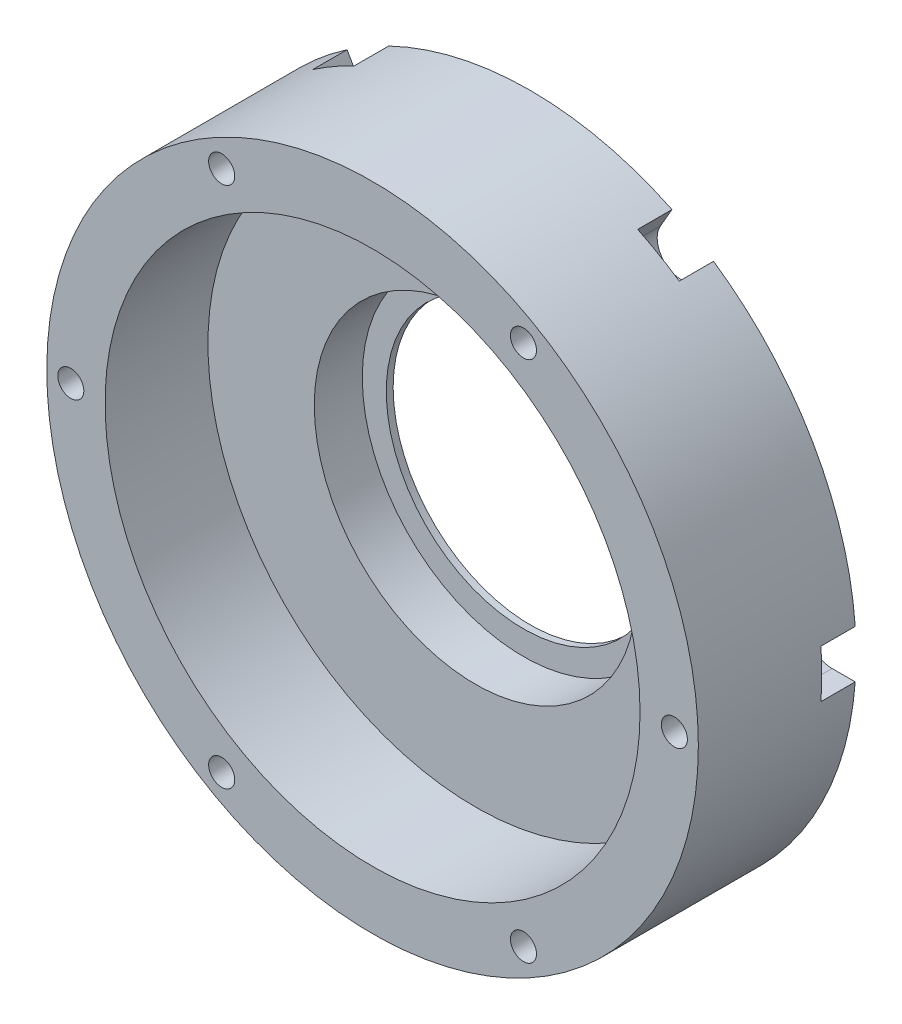
SolidWorks part; units mm, degrees
ref_plane "Front Plane" through (0, 0, 0) normal (0, 0, 1) x (1, 0, 0)
ref_plane "Top Plane" through (0, 0, 0) normal (0, 1, 0) x (1, 0, 0)
ref_plane "Right Plane" through (0, 0, 0) normal (1, 0, 0) x (0, 0, -1)
sketch "Sketch1" plane through (0, 0, 0) normal (0, 0, 1) x (1, 0, 0)
  circle A0 centre (0, 0) radius 47.5
  circle A1 centre (0, 0) radius 39
  dimension "D1" = 95
  dimension "D2" = 8.5
extrude "Boss-Extrude1" add sketch "Sketch1" along normal blind 15
sketch "Sketch4" plane through (0, 0, 0) normal (0, 0, -1) x (-1, 0, 0)
  circle A0 centre (0, 0) radius 47.5
  circle A1 centre (0, 0) radius 20
  dimension "D1" = 40
extrude "Boss-Extrude2" add sketch "Sketch4" along normal blind 8
sketch "Sketch5" plane through (0, 0, 0) normal (0, 0, 1) x (1, 0, 0)
  circle A0 centre (0, 0) radius 23.5
  dimension "D1" = 47
extrude "Cut-Extrude3" cut sketch "Sketch5" against normal blind 7
sketch "Sketch6" plane through (0, 0, 15) normal (0, 0, 1) x (1, 0, 0)
  circle A1 centre (44, 0) radius 1.9
  circle A2 centre (0, 0) radius 44
  circle A3 centre (0, 0) radius 44 construction
  circle A4 centre (22, -38.1051) radius 1.9
  circle A5 centre (-22, -38.1051) radius 1.9
  circle A6 centre (-44, 0) radius 1.9
  circle A7 centre (-22, 38.1051) radius 1.9
  circle A8 centre (22, 38.1051) radius 1.9
  point P17 (0, 0)
  dimension "D2" = 3.8
  dimension "D1" = 3.5
  dimension "D3" = 6
extrude "Cut-Extrude4" cut sketch "Sketch6" against normal through all
sketch "Sketch7" plane through (0, 0, -8) normal (0, 0, -1) x (-1, 0, 0)
  line L0 (44, 3.5) -> (47.3709, 3.5)
  line L1 (44, -3.5) -> (47.3709, -3.5)
  line L2 (25.0311, -36.3551) -> (26.7165, -39.2744)
  line L3 (18.9689, -39.8551) -> (20.6543, -42.7744)
  line L4 (-18.9689, -39.8551) -> (-20.6543, -42.7744)
  line L5 (-25.0311, -36.3551) -> (-26.7165, -39.2744)
  line L6 (-44, -3.5) -> (-47.3709, -3.5)
  line L7 (-44, 3.5) -> (-47.3709, 3.5)
  line L8 (-25.0311, 36.3551) -> (-26.7165, 39.2744)
  line L9 (-18.9689, 39.8551) -> (-20.6543, 42.7744)
  line L10 (18.9689, 39.8551) -> (20.6543, 42.7744)
  line L11 (25.0311, 36.3551) -> (26.7165, 39.2744)
  arc A0 (44, 3.5) -> (44, -3.5) centre (44, 0) ccw
  circle A1 centre (0, 0) radius 47.5 construction
  arc A2 (47.3709, -3.5) -> (47.3709, 3.5) centre (0, 0) ccw
  arc A3 (20.6543, -42.7744) -> (26.7165, -39.2744) centre (0, 0) ccw
  arc A4 (25.0311, -36.3551) -> (18.9689, -39.8551) centre (22, -38.1051) ccw
  arc A5 (-26.7165, -39.2744) -> (-20.6543, -42.7744) centre (0, 0) ccw
  arc A6 (-18.9689, -39.8551) -> (-25.0311, -36.3551) centre (-22, -38.1051) ccw
  arc A7 (-47.3709, 3.5) -> (-47.3709, -3.5) centre (0, 0) ccw
  arc A8 (-44, -3.5) -> (-44, 3.5) centre (-44, 0) ccw
  arc A9 (-20.6543, 42.7744) -> (-26.7165, 39.2744) centre (0, 0) ccw
  arc A10 (-25.0311, 36.3551) -> (-18.9689, 39.8551) centre (-22, 38.1051) ccw
  arc A11 (26.7165, 39.2744) -> (20.6543, 42.7744) centre (0, 0) ccw
  arc A12 (18.9689, 39.8551) -> (25.0311, 36.3551) centre (22, 38.1051) ccw
  point P35 (0, 0)
  dimension "D1" = 7
  dimension "D2" = 6
extrude "Cut-Extrude5" cut sketch "Sketch7" against normal blind 5
